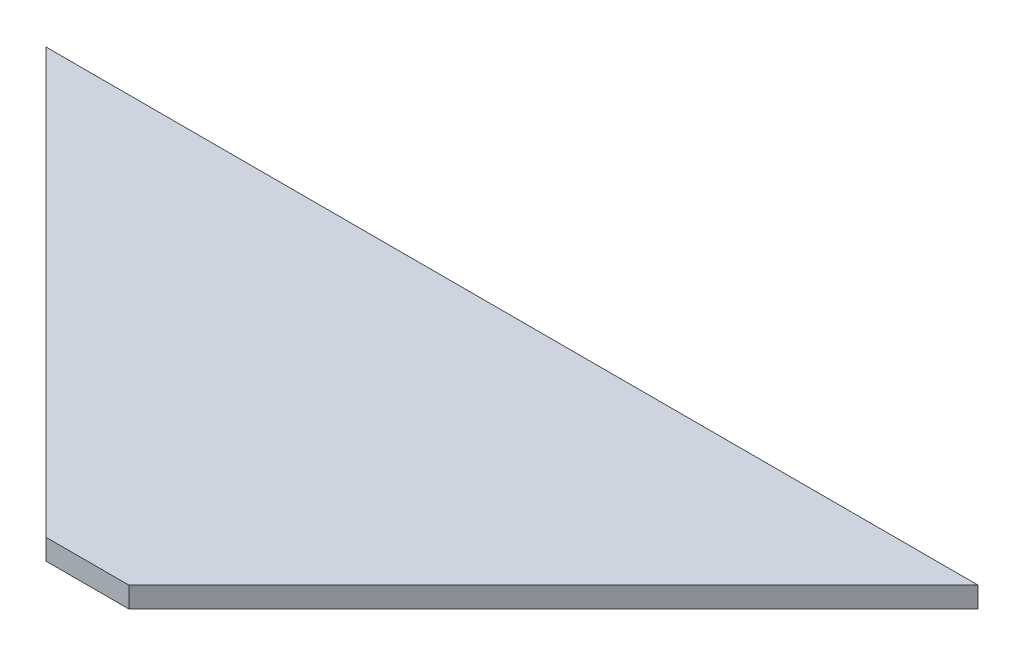
SolidWorks part; units mm, degrees
ref_plane "Front Plane" through (0, 0, 0) normal (0, 0, 1) x (1, 0, 0)
ref_plane "Top Plane" through (0, 0, 0) normal (0, 1, 0) x (1, 0, 0)
ref_plane "Right Plane" through (0, 0, 0) normal (1, 0, 0) x (0, 0, -1)
sketch "Sketch1" plane through (0, 0, 0) normal (0, 1, 0) x (1, 0, 0)
  line L20 (-22.5, 22.5) -> (22.5, 22.5)
  line L21 (22.5, 22.5) -> (2, 2)
  line L22 (2, 2) -> (-2, 2)
  line L39 (-2, 2) -> (-22.5, 22.5)
  line L44 (0, 0) -> (0, 22.5) construction
  line L45 (2, 2) -> (0, 0) construction
  line L46 (0, 0) -> (0, 2) construction
  line L51 (0, 2) -> (2, 2) construction
  line L53 (-7.5, 22.5) -> (7.5, 22.5) construction
  line L58 (-7.5, 22.5) -> (-7.5, 7.5) construction
  line L59 (-7.5, 7.5) -> (7.5, 7.5) construction
  line L60 (7.5, 22.5) -> (7.5, 7.5) construction
  line L61 (-7.5, 22.5) -> (7.5, 7.5) construction
  line L62 (-7.5, 7.5) -> (7.5, 22.5) construction
  point P7 (0, 22.5)
  point P8 (0, 2)
  point P12 (0, 15)
  dimension "D2" = 45
  dimension "D3" = 45
  dimension "D1" = 28.9914
  dimension "D4" = 2
  dimension "D5" = 15
  dimension "D6" = 15
extrude "Screen triangle" add sketch "Sketch1" along normal blind 1
equation "\"D1@Sketch1\"=\"total hypotenuse\""
equation "\"D2@Sketch1\"=\"screen width\""
equation "\"screen width\"= 45.00mm"
equation "\"screen height\"= 85.00mm"
equation "\"top cutoff\"= 2.00mm"
equation "\"A\"= \"screen width\" / 2"
equation "\"B\"= \"screen width\" / 2"
equation "\"screen hypotenuse\"= sqr ( ( \"A\" * \"A\" ) + ( \"B\" * \"B\" ) )"
equation "\"a2\"= \"top cutoff\" "
equation "\"b2\"= \"top cutoff\""
equation "\"top cutoff hypotenuse\"= sqr ( ( \"a2\" * \"a2\" ) + ( \"b2\" * \"b2\" ) )"
equation "\"total hypotenuse\"= \"screen hypotenuse\" - \"top cutoff hypotenuse\""
equation "\"image display width\"= ( \"A\" / 3 ) * 2"
equation "\"image display height\"= ( \"B\" / 3 ) * 2"
